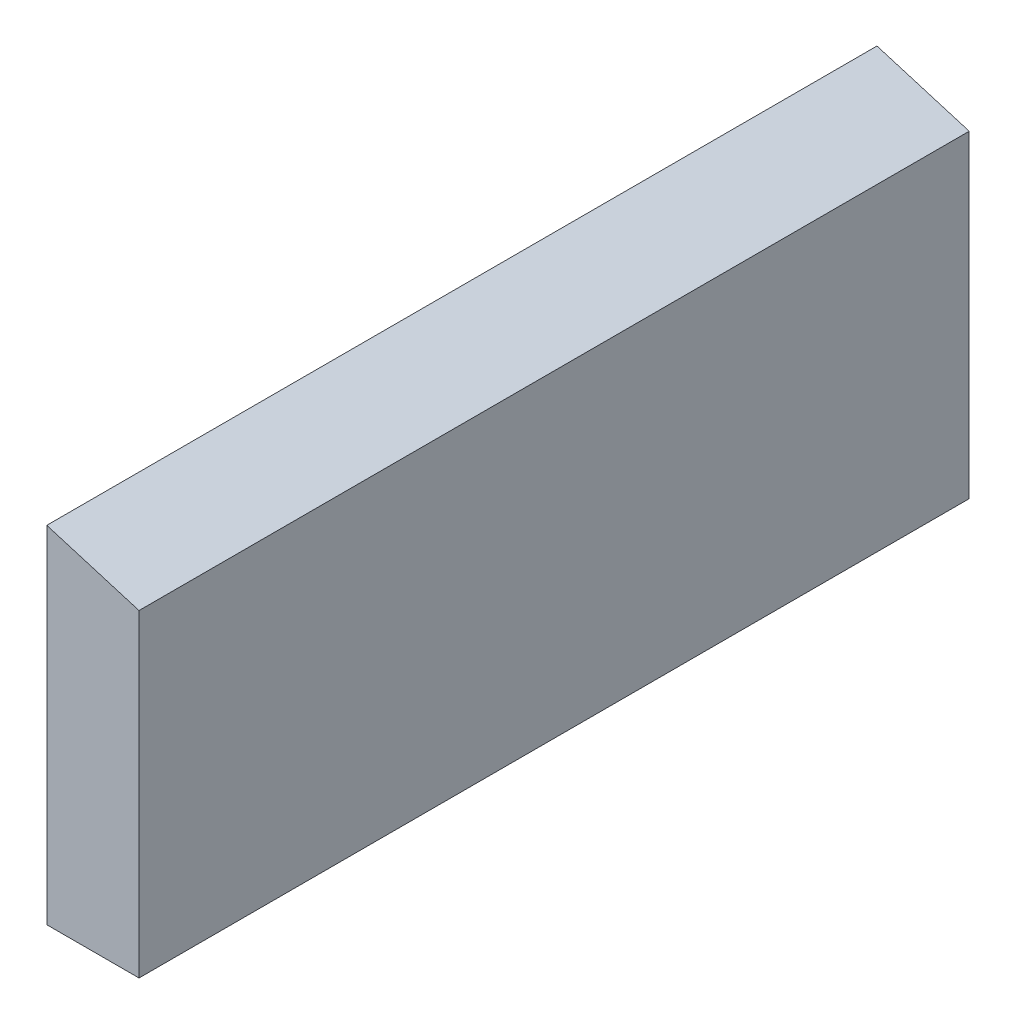
SolidWorks part; units mm, degrees
material "Balsa"
ref_plane "Front Plane" through (0, 0, 0) normal (0, 0, 1) x (1, 0, 0)
ref_plane "Top Plane" through (0, 0, 0) normal (0, 1, 0) x (1, 0, 0)
ref_plane "Right Plane" through (0, 0, 0) normal (1, 0, 0) x (0, 0, -1)
other "Bounding Box"
ref_plane "Default Plane" through (-20, 0, 180) normal (0, 1, 0) x (1, 0, 0)
sketch "Sketch1" plane through (0, 0, 0) normal (0, 0, 1) x (1, 0, 0)
  line L0 (0, 0) -> (-20, 0)
  line L1 (-20, 0) -> (-20, 75)
  line L2 (-20, 75) -> (0, 69)
  line L3 (0, 69) -> (0, 0)
  dimension "D1" = 20
  dimension "D2" = 75
  dimension "D3" = 69
extrude "Boss-Extrude1" add sketch "Sketch1" along normal blind 180
